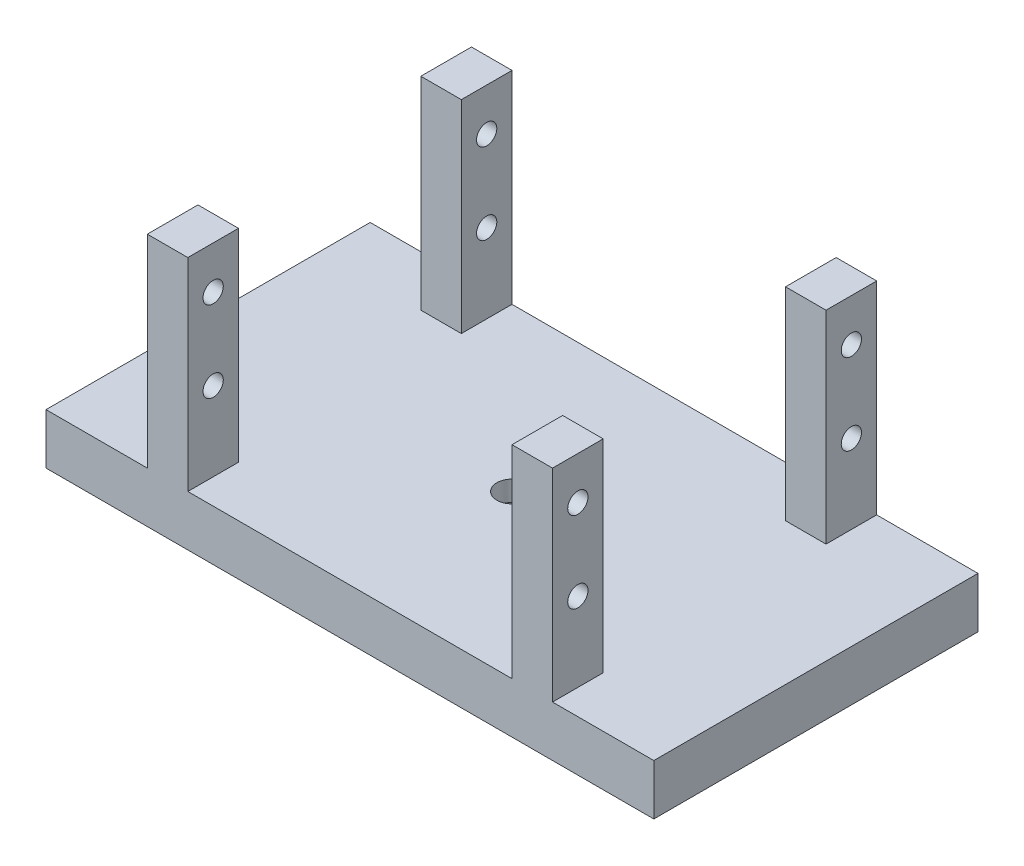
SolidWorks part; units mm, degrees
ref_plane "Front Plane" through (0, 0, 0) normal (0, 0, 1) x (1, 0, 0)
ref_plane "Top Plane" through (0, 0, 0) normal (0, 1, 0) x (1, 0, 0)
ref_plane "Right Plane" through (0, 0, 0) normal (1, 0, 0) x (0, 0, -1)
sketch "Sketch1" plane through (0, 0, 0) normal (0, 1, 0) x (1, 0, 0)
  line L1 (-30, 16) -> (30, 16)
  line L2 (-30, 16) -> (-30, -16)
  line L3 (-30, -16) -> (30, -16)
  line L4 (30, 16) -> (30, -16)
  line L5 (-30, 16) -> (30, -16) construction
  line L6 (-30, -16) -> (30, 16) construction
  circle A1 centre (0, 0) radius 1.5
  dimension "D1" = 60
  dimension "D2" = 3
  dimension "D3" = 32
extrude "Boss-Extrude1" add sketch "Sketch1" along normal blind 5
sketch "Sketch2" plane through (0, 0, 0) normal (0, -1, 0) x (1, 0, 0)
  circle A0 centre (0, 0) radius 4
  dimension "D1" = 8
extrude "Cut-Extrude1" cut sketch "Sketch2" against normal blind 3
sketch "Sketch3" plane through (0, 5, 0) normal (0, 1, 0) x (1, 0, 0)
  line L0 (0, 0) -> (0, -25.3091) construction
  line L1 (-20, 16) -> (-16, 16)
  line L2 (-20, 16) -> (-20, -16)
  line L3 (-20, -16) -> (-16, -16)
  line L4 (-16, 16) -> (-16, -16)
  line L5 (-20, 16) -> (-16, -16) construction
  line L6 (-20, -16) -> (-16, 16) construction
  line L7 (20, -16) -> (16, -16)
  line L8 (16, 16) -> (16, -16)
  line L9 (20, 16) -> (16, 16)
  line L10 (20, 16) -> (20, -16)
  point P0 (-18, 0)
  dimension "D1" = 32
  dimension "D2" = 4
  dimension "D3" = 18
extrude "Boss-Extrude2" add sketch "Sketch3" along normal blind 20
sketch "Sketch4" plane through (-20, 0, 0) normal (-1, 0, 0) x (0, 0, 1)
  line L0 (-16, 5) -> (16, 5) construction
  line L1 (-16, 25) -> (-16, 5) construction
  line L2 (16, 25) -> (16, 5) construction
  line L3 (-11, 25) -> (11, 25)
  line L4 (-11, 25) -> (-11, 5)
  line L5 (-11, 5) -> (11, 5)
  line L6 (11, 25) -> (11, 5)
  line L7 (-11, 25) -> (11, 5) construction
  line L8 (-11, 5) -> (11, 25) construction
  circle A0 centre (-13.5, 20.8) radius 1
  circle A1 centre (-13.5, 12.8) radius 1
  circle A2 centre (13.5, 20.8) radius 1
  circle A3 centre (13.5, 12.8) radius 1
  point P15 (0, 15)
  dimension "D1" = 2
  dimension "D2" = 7.8
  dimension "D3" = 27
  dimension "D4" = 2.5
  dimension "D5" = 8
  dimension "D6" = 20
  dimension "D7" = 5
extrude "Cut-Extrude2" cut sketch "Sketch4" against normal through all
